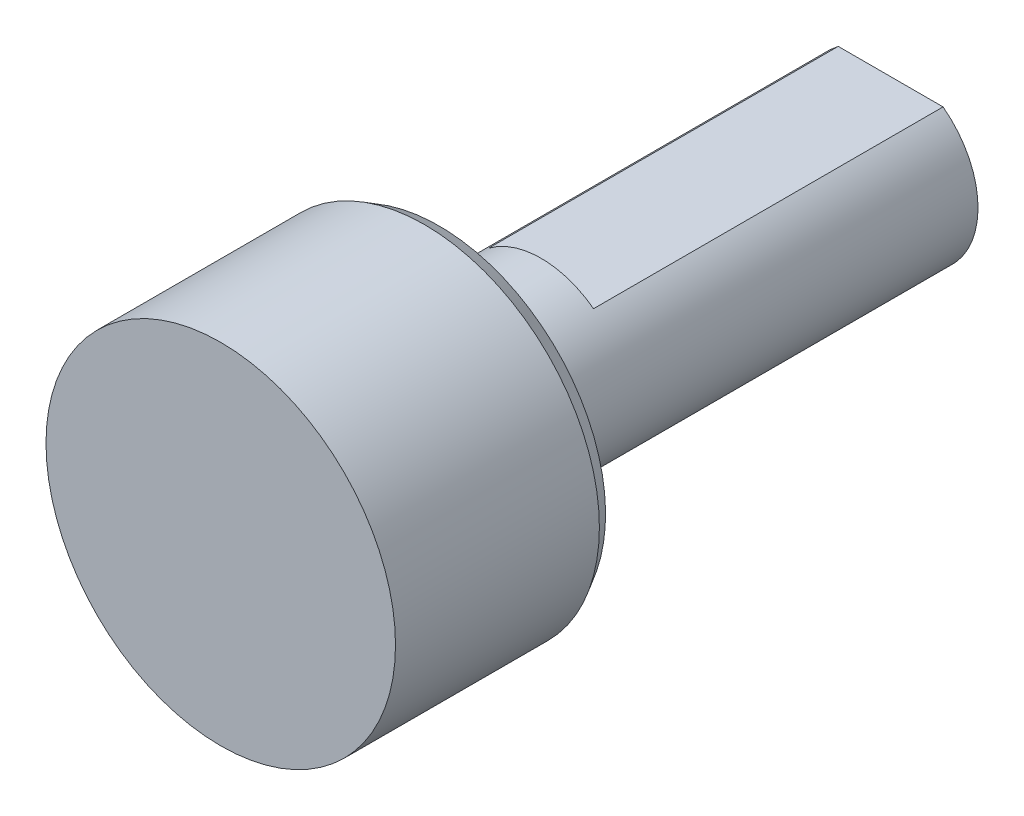
SolidWorks part; units mm, degrees
material "ABS"
ref_plane "Alzado" through (0, 0, 0) normal (0, 0, 1) x (1, 0, 0)
ref_plane "Planta" through (0, 0, 0) normal (0, 1, 0) x (1, 0, 0)
ref_plane "Vista lateral" through (0, 0, 0) normal (1, 0, 0) x (0, 0, -1)
sketch "Croquis2" plane through (0, 0, 7) normal (-1, 0, 0) x (0, 0, 1)
  line L0 (-7, 0) -> (-30, 0)
  line L2 (-30, 0) -> (-30, 3)
  line L3 (-30, 3) -> (-14.5, 3)
  line L4 (-14.5, 3) -> (-14.5, 5.7113)
  line L5 (-14.5, 5.7113) -> (-14, 6)
  line L6 (-7, 0) -> (-7, 6)
  line L7 (-14, 6) -> (-7, 6)
  dimension "D1" = 3
  dimension "D2" = 6
  dimension "D3" = 7.5
  dimension "D4" = 15.5
  dimension "D5" = 30
  dimension "D6" = 7
revolve "Revolución1" add sketch "Croquis2" angle 360 about L0
sketch "Croquis5" plane through (0, 0, 0) normal (1, 0, 0) x (0, 0, -1)
  line L1 (23, 3) -> (11, 3)
  line L2 (23, 3) -> (23, 2.4)
  line L3 (23, 2.4) -> (11, 2.4)
  line L4 (11, 3) -> (11, 2.4)
  dimension "D1" = 12
  dimension "D2" = 0.6
extrude "Cortar-Extruir2" cut sketch "Croquis5" against normal mid plane 6
